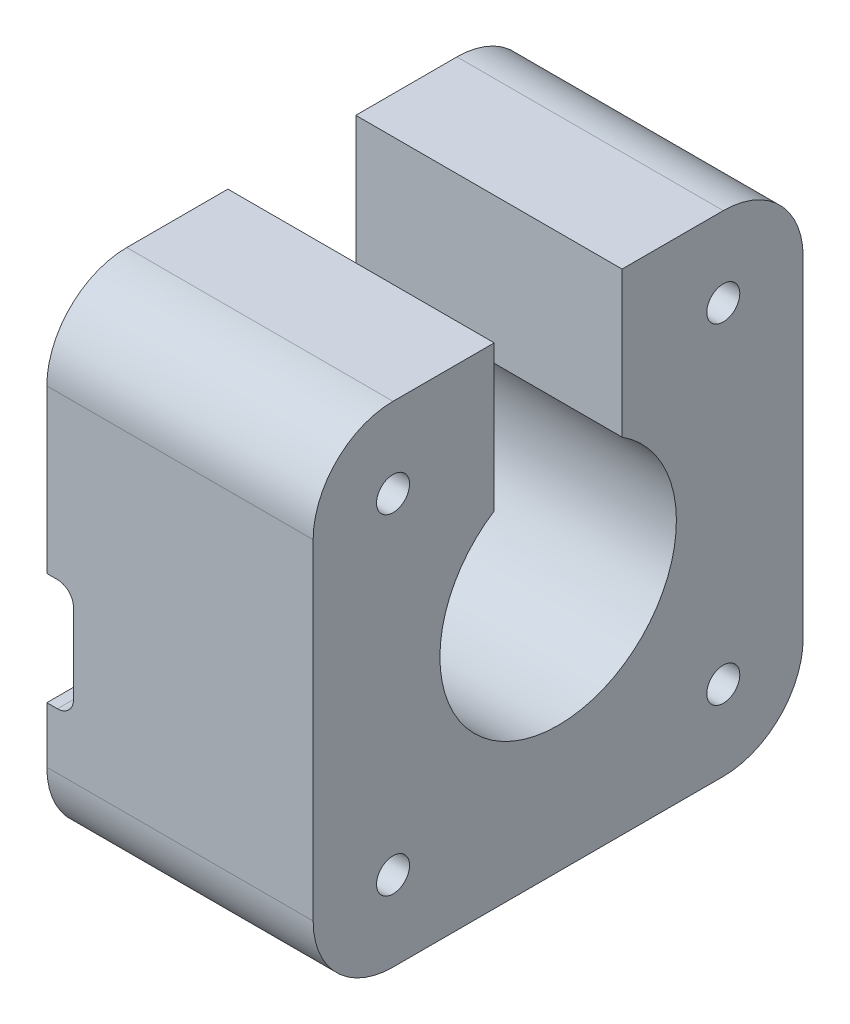
SolidWorks part; units mm, degrees
ref_plane "Alzado" through (0, 0, 0) normal (0, 0, 1) x (1, 0, 0)
ref_plane "Planta" through (0, 0, 0) normal (0, 1, 0) x (1, 0, 0)
ref_plane "Vista lateral" through (0, 0, 0) normal (1, 0, 0) x (0, 0, -1)
sketch "Croquis1" plane through (0, 0, 0) normal (1, 0, 0) x (0, 0, -1)
  line L0 (0, -17.3963) -> (0, 17.3963) construction
  line L1 (20.5983, 0) -> (-20.5983, 0) construction
  line L2 (-15.5, 23) -> (15.5, 23)
  line L3 (-23, 15.5) -> (-23, -15.5)
  line L4 (-15.5, -23) -> (15.5, -23)
  line L5 (23, -15.5) -> (23, 15.5)
  circle A0 centre (0, 0) radius 11.1
  arc A1 (-15.5, 23) -> (-23, 15.5) centre (-15.5, 15.5) ccw
  arc A2 (23, 15.5) -> (15.5, 23) centre (15.5, 15.5) ccw
  arc A3 (15.5, -23) -> (23, -15.5) centre (15.5, -15.5) ccw
  arc A4 (-23, -15.5) -> (-15.5, -23) centre (-15.5, -15.5) ccw
  circle A5 centre (-15.5, 15.5) radius 1.55
  circle A6 centre (15.5, 15.5) radius 1.55
  circle A7 centre (15.5, -15.5) radius 1.55
  circle A8 centre (-15.5, -15.5) radius 1.55
  point P6 (0, 0)
  point P9 (0, 0)
  dimension "D1" = 7.5
  dimension "D4" = 22.2
  dimension "D5" = 3.1
  dimension "D2" = 31
  dimension "D3" = 31
extrude "Saliente-Extruir1" add sketch "Croquis1" along normal blind 25
sketch "Croquis2" plane through (25, 0, 0) normal (1, 0, 0) x (0, 0, -1)
  line L0 (0, 23) -> (0, 11.1) construction
  line L1 (15.5, 23) -> (-15.5, 23) construction
  line L2 (-6, 23) -> (-6, 9.3386)
  line L3 (6, 23) -> (6, 9.3386)
  line L4 (-6, 23) -> (6, 23)
  circle A0 centre (0, 0) radius 11.1 construction
  arc A1 (6, 9.3386) -> (-6, 9.3386) centre (0, 0) ccw
  dimension "D1" = 12
extrude "Cortar-Extruir1" cut sketch "Croquis2" against normal through all
sketch "Croquis3" plane through (0, 0, -23) normal (0, 0, -1) x (-1, 0, 0)
  line L0 (0, 0) -> (-25, 0) construction
  line L1 (-25, -15.5) -> (-25, 15.5) construction
  line L2 (0, 0.25) -> (-1, 0.25)
  line L3 (0, -15.5) -> (0, 15.5) construction
  line L4 (-2.5, -1.25) -> (-2.5, -8.75)
  line L5 (-1, -10.25) -> (0, -10.25)
  line L6 (-2.5, -5) -> (0, -5) construction
  line L7 (0, 0.25) -> (0, -10.25)
  arc A0 (-1, 0.25) -> (-2.5, -1.25) centre (-1, -1.25) ccw
  arc A1 (-2.5, -8.75) -> (-1, -10.25) centre (-1, -8.75) ccw
  dimension "D2" = 1.5
  dimension "D1" = 2.5
  dimension "D3" = 5
  dimension "D4" = 10.5
extrude "Cortar-Extruir2" cut sketch "Croquis3" against normal through all
